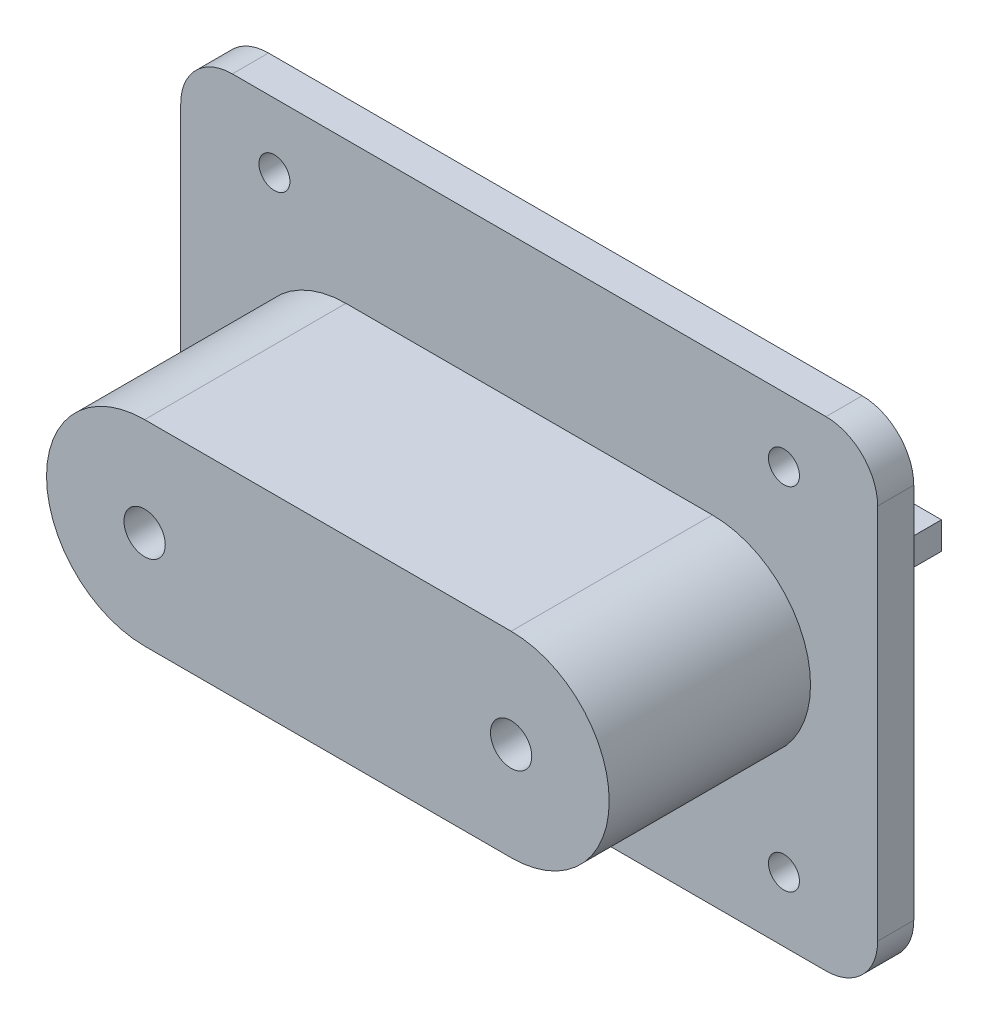
SolidWorks part; units mm, degrees
material "Custom Plastic"
ref_plane "X-Y Datum" through (0, 0, 0) normal (0, 0, 1) x (1, 0, 0)
ref_plane "X-Z Datum" through (0, 0, 0) normal (0, 1, 0) x (1, 0, 0)
ref_plane "Y-Z Datum" through (0, 0, 0) normal (1, 0, 0) x (0, 0, -1)
sketch "Sketch1" plane through (0, 0, 0) normal (0, 0, 1) x (1, 0, 0)
  line L1 (-67.5, -46.5) -> (67.5, -46.5)
  line L2 (-67.5, -46.5) -> (-67.5, 46.5)
  line L3 (-67.5, 46.5) -> (67.5, 46.5)
  line L4 (67.5, -46.5) -> (67.5, 46.5)
  line L5 (-67.5, -46.5) -> (67.5, 46.5) construction
  line L6 (-67.5, 46.5) -> (67.5, -46.5) construction
  line L7 (-49.3548, -34) -> (49.3548, -34)
  line L8 (-49.3548, -34) -> (-49.3548, 34)
  line L9 (-49.3548, 34) -> (49.3548, 34)
  line L10 (49.3548, -34) -> (49.3548, 34)
  line L11 (-49.3548, -34) -> (49.3548, 34) construction
  line L12 (-49.3548, 34) -> (49.3548, -34) construction
  circle A0 centre (-49.3548, 34) radius 3
  circle A1 centre (49.3548, 34) radius 3
  circle A2 centre (-49.3548, -34) radius 3
  circle A3 centre (49.3548, -34) radius 3
  point P0 (0, 0)
  point P6 (0, 0)
  dimension "D3" = 68
  dimension "D4" = 6
  dimension "D1" = 135
  dimension "D2" = 93
extrude "Boss-Extrude1" add sketch "Sketch1" along normal blind 7 contours L1 L4 L3 L2 A3 L7 A2 L8 A0 L9 A1 L10 | A3 L10 A1 L9 A0 L8 A2 L7
sketch "Sketch2" plane through (0, 0, 7) normal (0, 0, 1) x (1, 0, 0)
  line L0 (-35.5, 0) -> (35.5, 0) construction
  line L1 (-35.5, 19) -> (35.5, 19)
  line L4 (-35.5, -19) -> (35.5, -19)
  arc A2 (-35.5, 19) -> (-35.5, -19) centre (-35.5, 0) ccw
  arc A3 (35.5, -19) -> (35.5, 19) centre (35.5, 0) ccw
  circle A4 centre (-35.5, 0) radius 4
  circle A5 centre (35.5, 0) radius 4
  point P3 (0, 0)
  dimension "D1" = 8
  dimension "D2" = 71
extrude "Boss-Extrude2" add sketch "Sketch2" along normal blind 39
fillet "Fillet1" radius 10 4 edges at (67.5, 46.5, 3.5) (67.5, -46.5, 3.5) (-67.5, -46.5, 3.5) (-67.5, 46.5, 3.5)
sketch "Sketch3" plane through (0, 0, 0) normal (0, 0, -1) x (-1, 0, 0)
  circle A0 centre (-35.5, 0) radius 8
  circle A1 centre (35.5, 0) radius 8
extrude "Boss-Extrude3" add sketch "Sketch3" along normal blind 8
sketch "Sketch4" plane through (0, 0, -8) normal (0, 0, -1) x (-1, 0, 0)
  line L0 (0, 43.0151) -> (0, -43.0151) construction
  line L5 (-41.8678, 2.3782) -> (-28.5153, 2.3782)
  line L6 (-41.8678, 2.3782) -> (-41.8678, -2.9112)
  line L7 (-41.8678, -2.9112) -> (-28.5153, -2.9112)
  line L8 (-28.5153, 2.3782) -> (-28.5153, -2.9112)
  line L9 (41.8678, -2.9112) -> (28.5153, -2.9112)
  line L10 (28.5153, 2.3782) -> (28.5153, -2.9112)
  line L11 (41.8678, 2.3782) -> (28.5153, 2.3782)
  line L12 (41.8678, 2.3782) -> (41.8678, -2.9112)
  dimension "D1" = 13.3525
  dimension "D2" = 5.2894
extrude "Boss-Extrude4" add sketch "Sketch4" along normal blind 23
sketch "Sketch5" plane through (0, 2.3782, 0) normal (0, 1, 0) x (1, 0, 0)
  line L0 (35.1915, 31) -> (35.1915, 8) construction
  line L1 (28.5153, 31) -> (41.8678, 31) construction
  line L2 (28.5153, 8) -> (41.8678, 8) construction
  line L3 (0, -43.0151) -> (0, 43.0151) construction
  circle A0 centre (35.1915, 22.8909) radius 4
  circle A1 centre (-35.1915, 22.8909) radius 4
  dimension "D1" = 8
extrude "Cut-Extrude1" cut sketch "Sketch5" against normal blind 23
sketch "Sketch6" plane through (0, 0, 0) normal (0, 0, -1) x (-1, 0, 0)
  line L0 (55.1739, 0) -> (-55.1739, 0) construction
  line L1 (0, 43.0151) -> (0, -43.0151) construction
  circle A0 centre (-49.3548, 34) radius 6
  circle A1 centre (-49.3548, 34) radius 8.5
  circle A2 centre (-49.3548, -34) radius 8.5
  circle A3 centre (49.3548, -34) radius 8.5
  circle A4 centre (49.3548, 34) radius 8.5
  circle M3 centre (-49.3548, -34) radius 3
  circle M4 centre (49.3548, 34) radius 3
  circle M5 centre (-49.3548, 34) radius 3
  circle M6 centre (49.3548, -34) radius 3
extrude "Boss-Extrude5" add sketch "Sketch6" along normal blind 4 contours A2 M3 | A1 M5 | A4 M4 | A3 M6
